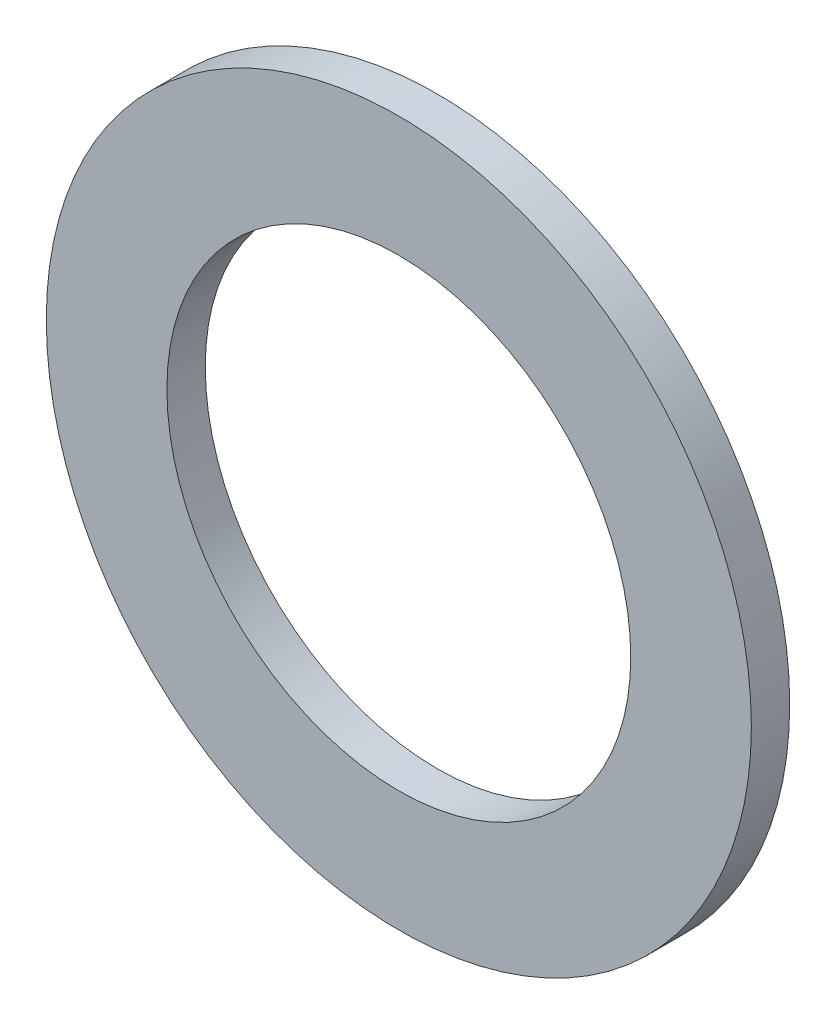
SolidWorks part; units mm, degrees
ref_plane "Front Plane" through (0, 0, 0) normal (0, 0, 1) x (1, 0, 0)
ref_plane "Top Plane" through (0, 0, 0) normal (0, 1, 0) x (1, 0, 0)
ref_plane "Right Plane" through (0, 0, 0) normal (1, 0, 0) x (0, 0, -1)
sketch "Sketch1" plane through (0, 0, 0) normal (0, 0, 1) x (1, 0, 0)
  line L0 (-7.239, 0) -> (7.239, 0) construction
  line L1 (0, -7.239) -> (0, 7.239) construction
  circle A0 centre (0, 0) radius 7.239
  circle A1 centre (0, 0) radius 4.7625
  point P4 (0, 0)
  point P9 (0, 0)
  dimension "ID" = 9.525
  dimension "OD" = 14.478
sketch "Sketch2" plane through (0, 0, 0) normal (1, 0, 0) x (0, 0, -1)
  line L0 (0.3937, 7.239) -> (-0.3937, 7.239) construction
  line L1 (0, 7.239) -> (0, -7.239) construction
  point P4 (0, 7.239)
  dimension "Thickness" = 0.7874
sketch "Sketch3" plane through (0, 0, 0) normal (0, 0, 1) x (1, 0, 0)
  line L0 (0, -7.239) -> (0, 7.239) construction
  circle A0 centre (0, 0) radius 7.239
  circle A1 centre (0, 0) radius 4.7625
  circle A2 centre (0, 0) radius 4.7625 construction
extrude "Boss-Extrude1" add sketch "Sketch3" along normal mid plane 0.7874
equation "\"D1@Boss-Extrude1\" = \"Thickness@Sketch2\""
